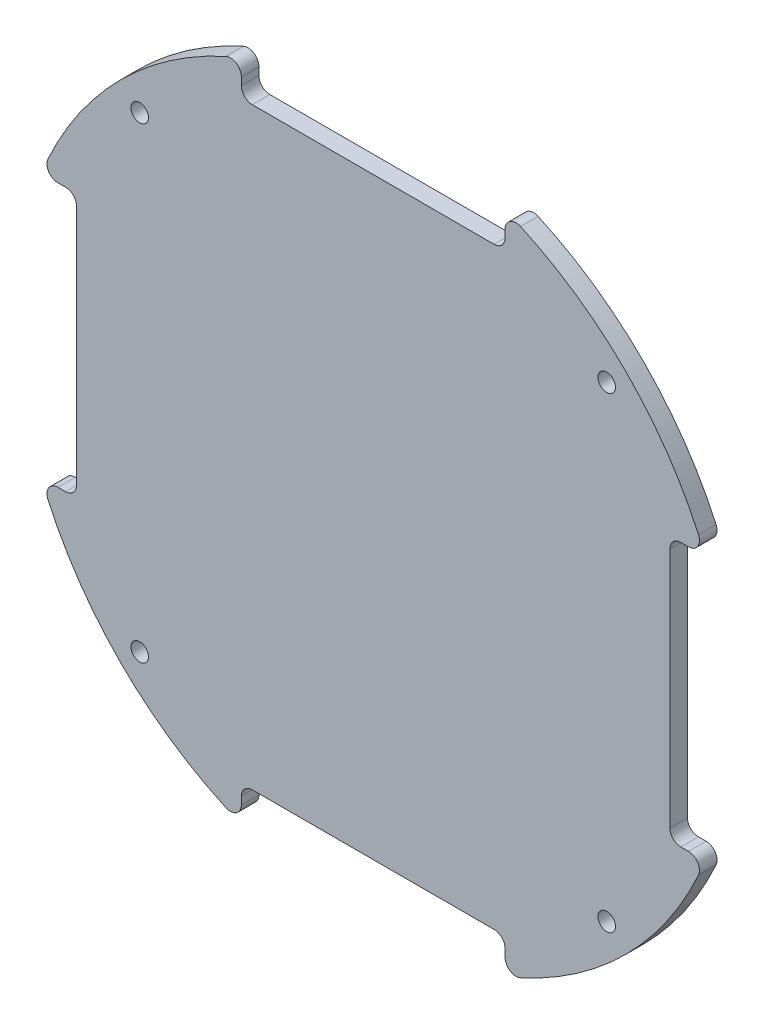
SolidWorks part; units mm, degrees
ref_plane "Front Plane" through (0, 0, 0) normal (0, 0, 1) x (1, 0, 0)
ref_plane "Top Plane" through (0, 0, 0) normal (0, 1, 0) x (1, 0, 0)
ref_plane "Right Plane" through (0, 0, 0) normal (1, 0, 0) x (0, 0, -1)
sketch "草图1" plane through (0, 0, 0) normal (0, 0, 1) x (1, 0, 0)
  circle A1 centre (0, 0) radius 32.5
extrude "凸台-拉伸1" add sketch "草图1" along normal blind 1.6
sketch "草图2" plane through (0, 0, 0) normal (0, 0, 1) x (1, 0, 0)
  line L0 (12, -27) -> (-12, -27)
  line L9 (27, 12) -> (32.5, 12)
  line L10 (27, 12) -> (27, -12)
  line L11 (27, -12) -> (32.5, -12)
  line L12 (32.5, 12) -> (32.5, -12)
  line L13 (12, -27) -> (12, -32.5)
  line L14 (12, -32.5) -> (-12, -32.5)
  line L15 (-12, -27) -> (-12, -32.5)
  line L16 (-27, -12) -> (-27, 12)
  line L17 (-27, -12) -> (-32.5, -12)
  line L18 (-32.5, -12) -> (-32.5, 12)
  line L19 (-27, 12) -> (-32.5, 12)
  line L20 (-12, 27) -> (12, 27)
  line L21 (-12, 27) -> (-12, 32.5)
  line L22 (-12, 32.5) -> (12, 32.5)
  line L23 (12, 27) -> (12, 32.5)
  point P19 (0, 0)
  dimension "D1" = 4
extrude "切除-拉伸1" cut sketch "草图2" along normal blind 1.6
sketch "草图3" plane through (0, 0, 1.6) normal (0, 0, 1) x (1, 0, 0)
  circle A0 centre (21.25, 21.25) radius 0.8
  circle A1 centre (21.25, -21.25) radius 0.8
  circle A2 centre (-21.25, -21.25) radius 0.8
  circle A3 centre (-21.25, 21.25) radius 0.8
  point P11 (0, 0)
  dimension "D1" = 4
extrude "切除-拉伸2" cut sketch "草图3" against normal blind 1.6
fillet "圆角1" radius 1 16 edges at (-12, 30.2035, 0.8) (-12, 27, 0.8) (12, 27, 0.8) (12, 30.2035, 0.8) (30.2035, 12, 0.8) (27, 12, 0.8) (27, -12, 0.8) (30.2035, -12, 0.8) (12, -30.2035, 0.8) (12, -27, 0.8) (-12, -27, 0.8) (-12, -30.2035, 0.8) (-30.2035, -12, 0.8) (-27, -12, 0.8) (-27, 12, 0.8) (-30.2035, 12, 0.8)
